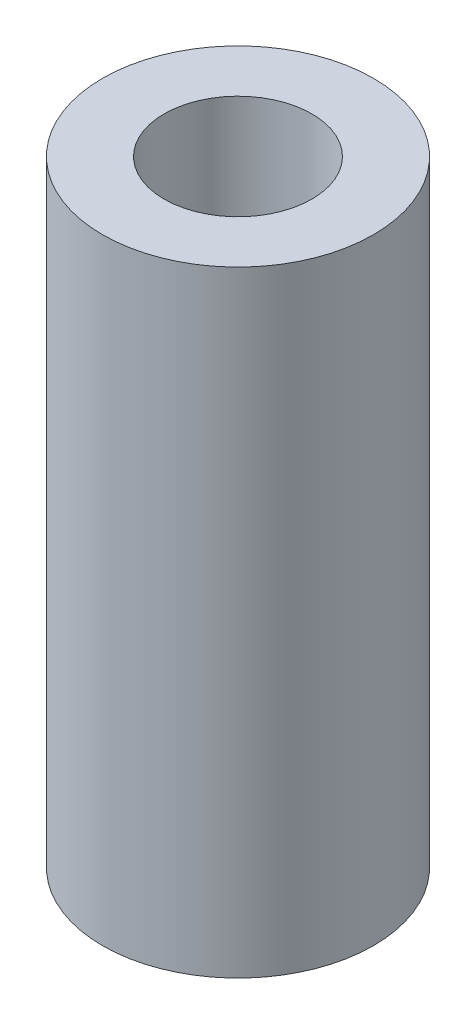
SolidWorks part; units mm, degrees
ref_plane "Front Plane" through (0, 0, 0) normal (0, 0, 1) x (1, 0, 0)
ref_plane "Top Plane" through (0, 0, 0) normal (0, 1, 0) x (1, 0, 0)
ref_plane "Right Plane" through (0, 0, 0) normal (1, 0, 0) x (0, 0, -1)
sketch "Sketch1" plane through (0, 0, 0) normal (0, 1, 0) x (1, 0, 0)
  circle A0 centre (0, 0) radius 1.8
  circle A1 centre (0, 0) radius 3.3
  dimension "D1" = 3.6
  dimension "D2" = 1.5
extrude "Boss-Extrude1" add sketch "Sketch1" along normal blind 15
